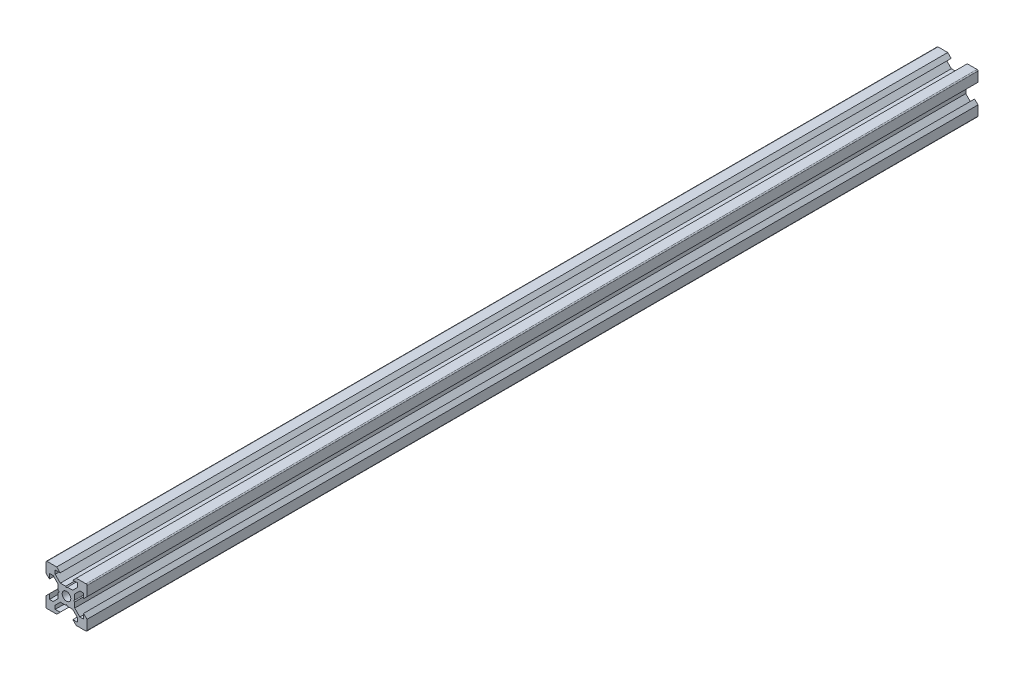
SolidWorks part; units mm, degrees
ref_plane "Front Plane" through (0, 0, 0) normal (0, 0, 1) x (1, 0, 0)
ref_plane "Top Plane" through (0, 0, 0) normal (0, 1, 0) x (1, 0, 0)
ref_plane "Right Plane" through (0, 0, 0) normal (1, 0, 0) x (0, 0, -1)
sketch "Sketch1" plane through (0, 0, 0) normal (0, 0, 1) x (1, 0, 0)
  line L0 (0, 11.7715) -> (0, -11.0375) construction
  line L1 (-10, 10) -> (10, 10) construction
  line L2 (-10, 10) -> (-10, -10) construction
  line L3 (-10, -10) -> (10, -10) construction
  line L4 (10, 10) -> (10, -10) construction
  line L5 (-10, 10) -> (10, -10) construction
  line L6 (-10, -10) -> (10, 10) construction
  line L7 (-5.5, 5.5) -> (5.5, 5.5) construction
  line L8 (-5.5, 5.5) -> (-5.5, -5.5) construction
  line L9 (-5.5, -5.5) -> (5.5, -5.5) construction
  line L10 (5.5, 5.5) -> (5.5, -5.5) construction
  line L11 (-5.5, 5.5) -> (5.5, -5.5) construction
  line L12 (-5.5, -5.5) -> (5.5, 5.5) construction
  line L13 (-10, 10) -> (-4.775, 10)
  line L14 (-4.775, 10) -> (-3.1, 8.325)
  line L15 (-3.1, 8.325) -> (-5.5, 8.325)
  line L16 (-5.5, 8.325) -> (-5.5, 6.525)
  line L17 (-5.5, 6.525) -> (-3, 4.025)
  line L18 (-3, 4.025) -> (3, 4.025)
  line L19 (-2.8044, 0) -> (3.0922, 0) construction
  line L20 (5.5, 6.525) -> (3, 4.025)
  line L21 (5.5, 8.325) -> (5.5, 6.525)
  line L22 (3.1, 8.325) -> (5.5, 8.325)
  line L23 (4.775, 10) -> (3.1, 8.325)
  line L24 (10, 10) -> (4.775, 10)
  line L25 (10, -10) -> (4.775, -10)
  line L26 (4.775, -10) -> (3.1, -8.325)
  line L27 (3.1, -8.325) -> (5.5, -8.325)
  line L28 (5.5, -8.325) -> (5.5, -6.525)
  line L29 (5.5, -6.525) -> (3, -4.025)
  line L30 (-3.1, -8.325) -> (-5.5, -8.325)
  line L31 (-3, -4.025) -> (3, -4.025)
  line L32 (-5.5, -6.525) -> (-3, -4.025)
  line L33 (-5.5, -8.325) -> (-5.5, -6.525)
  line L34 (-4.775, -10) -> (-3.1, -8.325)
  line L35 (-10, -10) -> (-4.775, -10)
  line L36 (-4.025, 3) -> (-4.025, -3)
  line L37 (-6.525, 5.5) -> (-4.025, 3)
  line L38 (-8.325, 5.5) -> (-6.525, 5.5)
  line L39 (-8.325, 3.1) -> (-8.325, 5.5)
  line L40 (-10, 4.775) -> (-8.325, 3.1)
  line L41 (-10, 10) -> (-10, 4.775)
  line L42 (-10, -10) -> (-10, -4.775)
  line L43 (-10, -4.775) -> (-8.325, -3.1)
  line L44 (-8.325, -3.1) -> (-8.325, -5.5)
  line L45 (-8.325, -5.5) -> (-6.525, -5.5)
  line L46 (-6.525, -5.5) -> (-4.025, -3)
  line L47 (10, -10) -> (10, -4.775)
  line L48 (10, -4.775) -> (8.325, -3.1)
  line L49 (8.325, -3.1) -> (8.325, -5.5)
  line L50 (8.325, -5.5) -> (6.525, -5.5)
  line L51 (6.525, -5.5) -> (4.025, -3)
  line L52 (4.025, 3) -> (4.025, -3)
  line L53 (6.525, 5.5) -> (4.025, 3)
  line L54 (8.325, 5.5) -> (6.525, 5.5)
  line L55 (8.325, 3.1) -> (8.325, 5.5)
  line L56 (10, 4.775) -> (8.325, 3.1)
  line L57 (10, 10) -> (10, 4.775)
  circle A0 centre (0, 0) radius 2.1
  point P0 (0, 0)
  point P6 (0, 0)
  point P23 (0, 4.025)
  dimension "D3" = 4.2
  dimension "D1" = 20
  dimension "D2" = 20
  dimension "D4" = 45
  dimension "D5" = 45
  dimension "D6" = 9.55
  dimension "D7" = 6.2
  dimension "D8" = 11
  dimension "D9" = 1.675
  dimension "D10" = 4.3
  dimension "D11" = 9.55
  dimension "D12" = 6.2
  dimension "D13" = 1.675
  dimension "D14" = 4.3
  dimension "D15" = 1.8
  dimension "D16" = 1.8
  dimension "D17" = 45
extrude "Boss-Extrude1" add sketch "Sketch1" along normal blind 435
fillet "Fillet1" radius 0.5 4 edges at (-10, -10, 217.5) (10, -10, 217.5) (10, 10, 217.5) (-10, 10, 217.5)
sketch "Sketch2" plane through (0, 0, 435) normal (0, 0, 1) x (1, 0, 0)
  line L0 (-0.8203, 0) -> (1.3478, 0) construction
  line L1 (0, 1.2196) -> (0, -1.1398) construction
  line L44 (-10, -4.775) -> (-10, -9.5)
  line L45 (-9.5, -10) -> (-4.775, -10)
  line L46 (-4.775, -10) -> (-3.1, -8.325)
  line L47 (-3.1, -8.325) -> (-5.5, -8.325)
  line L48 (-5.5, -8.325) -> (-5.5, -6.525)
  line L49 (-5.5, -6.525) -> (-3, -4.025)
  line L50 (-3, -4.025) -> (3, -4.025)
  line L51 (3, -4.025) -> (5.5, -6.525)
  line L52 (5.5, -6.525) -> (5.5, -8.325)
  line L53 (5.5, -8.325) -> (3.1, -8.325)
  line L54 (3.1, -8.325) -> (4.775, -10)
  line L55 (4.775, -10) -> (9.5, -10)
  line L56 (10, -9.5) -> (10, -4.775)
  line L57 (10, -4.775) -> (8.325, -3.1)
  line L58 (8.325, -3.1) -> (8.325, -5.5)
  line L59 (8.325, -5.5) -> (6.525, -5.5)
  line L60 (6.525, -5.5) -> (4.025, -3)
  line L61 (4.025, -3) -> (4.025, 3)
  line L62 (4.025, 3) -> (6.525, 5.5)
  line L63 (6.525, 5.5) -> (8.325, 5.5)
  line L64 (8.325, 5.5) -> (8.325, 3.1)
  line L65 (8.325, 3.1) -> (10, 4.775)
  line L66 (10, 4.775) -> (10, 9.5)
  line L67 (9.5, 10) -> (4.775, 10)
  line L68 (4.775, 10) -> (3.1, 8.325)
  line L69 (3.1, 8.325) -> (5.5, 8.325)
  line L70 (5.5, 8.325) -> (5.5, 6.525)
  line L71 (5.5, 6.525) -> (3, 4.025)
  line L72 (3, 4.025) -> (-3, 4.025)
  line L73 (-3, 4.025) -> (-5.5, 6.525)
  line L74 (-5.5, 6.525) -> (-5.5, 8.325)
  line L75 (-5.5, 8.325) -> (-3.1, 8.325)
  line L76 (-3.1, 8.325) -> (-4.775, 10)
  line L77 (-4.775, 10) -> (-9.5, 10)
  line L78 (-10, 9.5) -> (-10, 4.775)
  line L79 (-10, 4.775) -> (-8.325, 3.1)
  line L80 (-8.325, 3.1) -> (-8.325, 5.5)
  line L81 (-8.325, 5.5) -> (-6.525, 5.5)
  line L82 (-6.525, 5.5) -> (-4.025, 3)
  line L83 (-4.025, 3) -> (-4.025, -3)
  line L84 (-4.025, -3) -> (-6.525, -5.5)
  line L85 (-6.525, -5.5) -> (-8.325, -5.5)
  line L86 (-8.325, -5.5) -> (-8.325, -3.1)
  line L87 (-8.325, -3.1) -> (-10, -4.775)
  line L88 (-10, -4.775) -> (-10, -9.5)
  line L89 (-9.5, -10) -> (-4.775, -10)
  line L90 (-4.775, -10) -> (-3.1, -8.325)
  line L91 (-3.1, -8.325) -> (-5.5, -8.325)
  line L92 (-5.5, -8.325) -> (-5.5, -6.525)
  line L93 (-5.5, -6.525) -> (-3, -4.025)
  line L94 (-3, -4.025) -> (3, -4.025)
  line L95 (3, -4.025) -> (5.5, -6.525)
  line L96 (5.5, -6.525) -> (5.5, -8.325)
  line L97 (5.5, -8.325) -> (3.1, -8.325)
  line L98 (3.1, -8.325) -> (4.775, -10)
  line L99 (4.775, -10) -> (9.5, -10)
  line L100 (10, -9.5) -> (10, -4.775)
  line L101 (10, -4.775) -> (8.325, -3.1)
  line L102 (8.325, -3.1) -> (8.325, -5.5)
  line L103 (8.325, -5.5) -> (6.525, -5.5)
  line L104 (6.525, -5.5) -> (4.025, -3)
  line L105 (4.025, -3) -> (4.025, 3)
  line L106 (4.025, 3) -> (6.525, 5.5)
  line L107 (6.525, 5.5) -> (8.325, 5.5)
  line L108 (8.325, 5.5) -> (8.325, 3.1)
  line L109 (8.325, 3.1) -> (10, 4.775)
  line L110 (10, 4.775) -> (10, 9.5)
  line L111 (9.5, 10) -> (4.775, 10)
  line L112 (4.775, 10) -> (3.1, 8.325)
  line L113 (3.1, 8.325) -> (5.5, 8.325)
  line L114 (5.5, 8.325) -> (5.5, 6.525)
  line L115 (5.5, 6.525) -> (3, 4.025)
  line L116 (3, 4.025) -> (-3, 4.025)
  line L117 (-3, 4.025) -> (-5.5, 6.525)
  line L118 (-5.5, 6.525) -> (-5.5, 8.325)
  line L119 (-5.5, 8.325) -> (-3.1, 8.325)
  line L120 (-3.1, 8.325) -> (-4.775, 10)
  line L121 (-4.775, 10) -> (-9.5, 10)
  line L122 (-10, 9.5) -> (-10, 4.775)
  line L123 (-10, 4.775) -> (-8.325, 3.1)
  line L124 (-8.325, 3.1) -> (-8.325, 5.5)
  line L125 (-8.325, 5.5) -> (-6.525, 5.5)
  line L126 (-6.525, 5.5) -> (-4.025, 3)
  line L127 (-4.025, 3) -> (-4.025, -3)
  line L128 (-4.025, -3) -> (-6.525, -5.5)
  line L129 (-6.525, -5.5) -> (-8.325, -5.5)
  line L130 (-8.325, -5.5) -> (-8.325, -3.1)
  line L131 (-8.325, -3.1) -> (-10, -4.775)
  circle A0 centre (-4.025, 0) radius 0.4
  circle A1 centre (4.025, 0) radius 0.4
  circle A2 centre (0, 4.025) radius 0.4
  circle A3 centre (0, -4.025) radius 0.4
  arc A4 (-10, -9.5) -> (-9.5, -10) centre (-9.5, -9.5) ccw
  arc A5 (9.5, -10) -> (10, -9.5) centre (9.5, -9.5) ccw
  arc A6 (10, 9.5) -> (9.5, 10) centre (9.5, 9.5) ccw
  arc A7 (-9.5, 10) -> (-10, 9.5) centre (-9.5, 9.5) ccw
  arc A8 (-10, -9.5) -> (-9.5, -10) centre (-9.5, -9.5) ccw
  arc A9 (9.5, -10) -> (10, -9.5) centre (9.5, -9.5) ccw
  arc A10 (10, 9.5) -> (9.5, 10) centre (9.5, 9.5) ccw
  arc A11 (-9.5, 10) -> (-10, 9.5) centre (-9.5, 9.5) ccw
  dimension "D2" = 0.8
  dimension "D3" = 0.8
  dimension "D1" = 0
extrude "Cut-Extrude1" cut sketch "Sketch2" against normal through all contours L127 A0 | L116 A2 | A1 L105 | A3 L94
